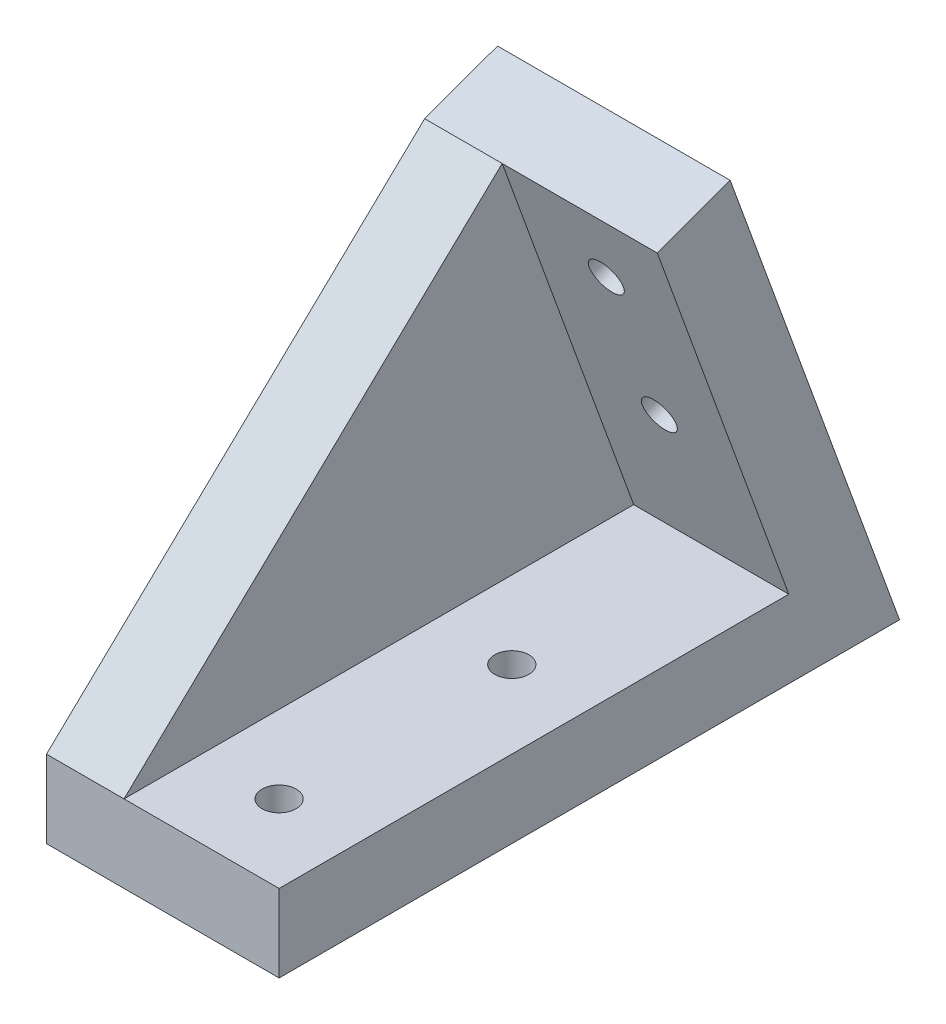
SolidWorks part; units mm, degrees
ref_plane "Front Plane" through (0, 0, 0) normal (0, 0, 1) x (1, 0, 0)
ref_plane "Top Plane" through (0, 0, 0) normal (0, 1, 0) x (1, 0, 0)
ref_plane "Right Plane" through (0, 0, 0) normal (1, 0, 0) x (0, 0, -1)
sketch "Sketch1" plane through (0, 0, 0) normal (0, 0, 1) x (1, 0, 0)
  line L1 (0, 0) -> (15, 0)
  line L2 (0, 0) -> (0, 30)
  line L3 (0, 30) -> (15, 30)
  line L4 (15, 0) -> (15, 30)
  dimension "D1" = 15
  dimension "D2" = 30
extrude "Boss-Extrude1" add sketch "Sketch1" along normal blind 40
sketch "Sketch2" plane through (15, 0, 0) normal (1, 0, 0) x (0, 0, -1)
  line L0 (0, 0) -> (-10.9191, 30)
  line L1 (-40, 30) -> (0, 30) construction
  line L2 (-10.9191, 30) -> (0, 30)
  line L3 (0, 30) -> (0, 0)
  dimension "D1" = 20
extrude "Cut-Extrude1" cut sketch "Sketch2" against normal blind 40
sketch "Sketch3" plane through (15, 0, 0) normal (1, 0, 0) x (0, 0, -1)
  line L0 (-10.9191, 30) -> (-15.6176, 28.2899)
  line L1 (-15.6176, 28.2899) -> (-7.1407, 5)
  line L2 (-40, 0) -> (0, 0) construction
  line L3 (-40, 30) -> (-10.9191, 30) construction
  line L5 (0, 0) -> (-10.9191, 30)
  line L6 (-40, 0) -> (-40, 5)
  line L7 (-40, 0) -> (-40, 30) construction
  line L8 (-40, 5) -> (-7.1407, 5)
  line L9 (0, 0) -> (-40, 0)
  dimension "D1" = 70
  dimension "D2" = 20
  dimension "D3" = 5
  dimension "D4" = 5
extrude "Boss-Extrude2" add sketch "Sketch3" along normal blind 10
sketch "Sketch5" plane through (0, 0, 0) normal (-1, 0, 0) x (0, 0, 1)
  line L0 (10.9191, 30) -> (40, 30)
  line L1 (40, 30) -> (40, 0)
  line L2 (40, 0) -> (0, 0)
  line L3 (0, 0) -> (10.9191, 30)
extrude "Cut-Extrude2" cut sketch "Sketch5" against normal blind 10
sketch "Sketch6" plane through (15, 0, 0) normal (1, 0, 0) x (0, 0, -1)
  line L0 (-15.6176, 28.2899) -> (-40, 5)
  line L1 (-40, 5) -> (-40, 30)
  line L2 (-40, 30) -> (-10.9191, 30)
  line L3 (-10.9191, 30) -> (-15.6176, 28.2899)
extrude "Cut-Extrude3" cut sketch "Sketch6" against normal blind 10
sketch "Sketch7" plane through (0, 0, 0) normal (0, -1, 0) x (1, 0, 0)
  line L0 (10, 40) -> (25, 40) construction
  line L1 (25, 40) -> (25, 0) construction
  circle A0 centre (20, 35) radius 1.1
  circle A1 centre (20, 20) radius 1.1
  dimension "D1" = 2.2
  dimension "D2" = 2.2
  dimension "D3" = 5
  dimension "D4" = 5
  dimension "D6" = 5
  dimension "D5" = 20
extrude "Cut-Extrude4" cut sketch "Sketch7" against normal blind 10
sketch "Sketch8" plane through (0, 0, 0) normal (0, 0.342, -0.9397) x (-1, 0, 0)
  line L0 (-25, 0) -> (-25, 31.9253) construction
  line L1 (-25, 31.9253) -> (-10, 31.9253) construction
  circle A0 centre (-20, 26.9253) radius 1.1
  circle A1 centre (-20, 16.9253) radius 1.1
  dimension "D1" = 2.2
  dimension "D2" = 2.2
  dimension "D3" = 5
  dimension "D4" = 5
  dimension "D5" = 5
  dimension "D6" = 15
extrude "Cut-Extrude5" cut sketch "Sketch8" against normal blind 10
